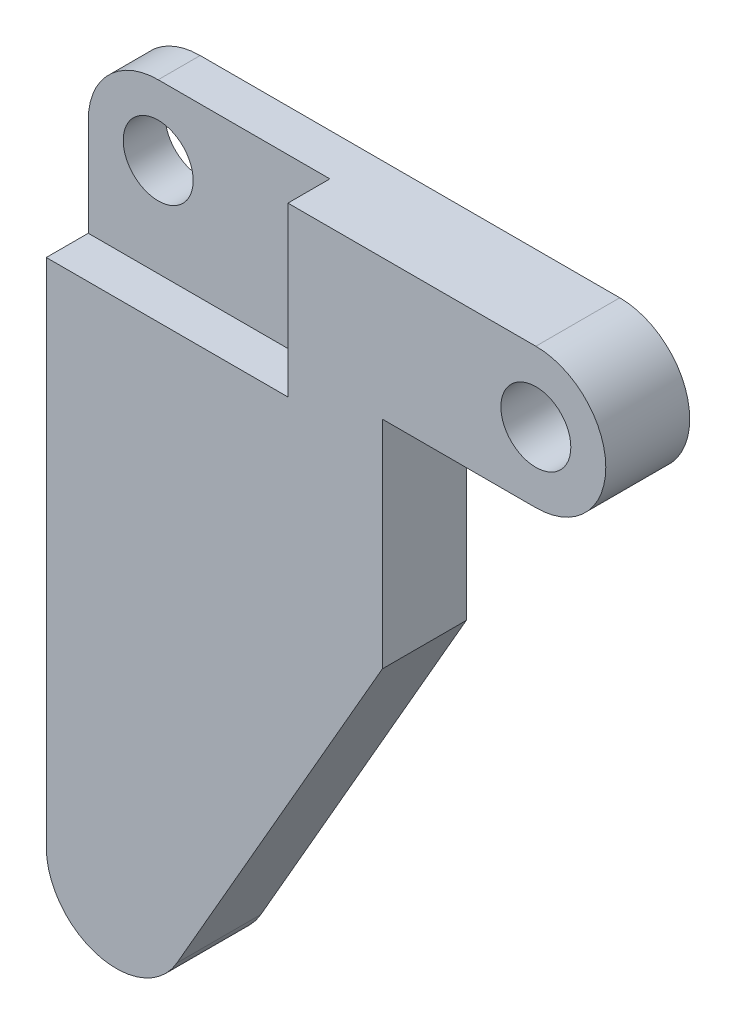
SolidWorks part; units mm, degrees
ref_plane "Front Plane" through (0, 0, 0) normal (0, 0, 1) x (1, 0, 0)
ref_plane "Top Plane" through (0, 0, 0) normal (0, 1, 0) x (1, 0, 0)
ref_plane "Right Plane" through (0, 0, 0) normal (1, 0, 0) x (0, 0, -1)
sketch "Sketch1" plane through (0, 0, 0) normal (0, 0, 1) x (1, 0, 0)
  line L0 (0, 0) -> (30, 0) construction
  line L1 (0, 0) -> (30, 0) construction
  line L2 (0, 5) -> (30, 5)
  line L3 (0, -5) -> (30, -5)
  line L4 (-5, 0) -> (-5, -43.5303)
  line L5 (4.3349, -46.022) -> (19.0262, -20.4631)
  line L6 (19.0262, -20.4631) -> (19.0262, -5)
  arc A0 (0, 5) -> (0, -5) centre (0, 0) ccw
  arc A1 (30, -5) -> (30, 5) centre (30, 0) ccw
  arc A2 (-5, -43.5303) -> (4.3349, -46.022) centre (0, -43.5303) ccw
  circle A3 centre (0, 0) radius 2.5
  circle A4 centre (30, 0) radius 2.5
  point P3 (15, 0)
  dimension "D2" = 5
  dimension "D3" = 5
  dimension "D1" = 30
extrude "Boss-Extrude1" add sketch "Sketch1" against normal blind 6 contours L4 A2 L5 L6 L3 A0 | L3 A1 L2 A0
sketch "Sketch3" plane through (0, 0, 0) normal (0, 0, 1) x (1, 0, 0)
  line L0 (12.2752, 5) -> (12.2752, -7.0042)
  line L1 (0, 5) -> (30, 5) construction
  line L2 (12.2752, -7.0042) -> (-5, -7.0042)
  line L3 (-5, 0) -> (-5, -43.5303) construction
  line L4 (-5, -7.0042) -> (-5, 0)
  line L6 (0, 5) -> (12.2752, 5)
  line L7 (0, 5) -> (30, 5) construction
  arc A0 (0, 5) -> (-5, 0) centre (0, 0) ccw
  point P12 (12.2752, 5)
extrude "Cut-Extrude2" cut sketch "Sketch3" against normal blind 3
